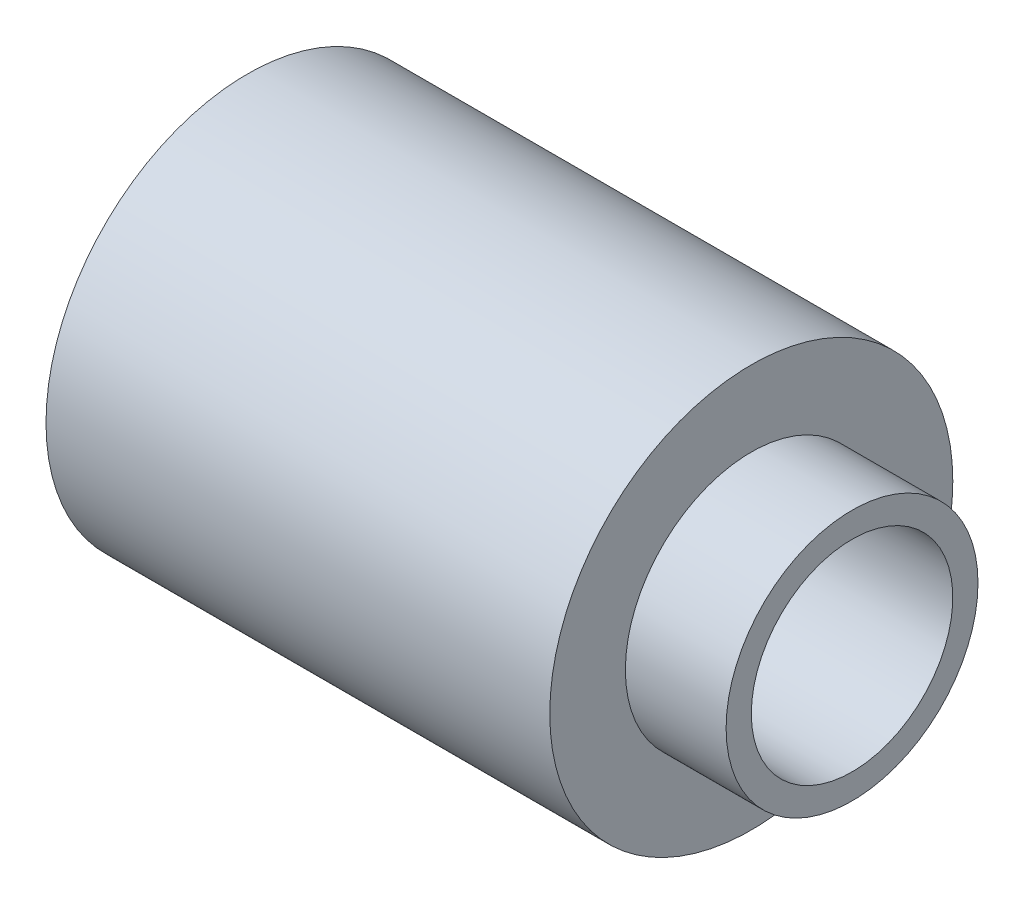
SolidWorks part; units mm, degrees
material "Alloy Steel"
ref_plane "Front Plane" through (0, 0, 0) normal (0, 0, 1) x (1, 0, 0)
ref_plane "Top Plane" through (0, 0, 0) normal (0, 1, 0) x (1, 0, 0)
ref_plane "Right Plane" through (0, 0, 0) normal (1, 0, 0) x (0, 0, -1)
sketch "Sketch1" plane through (0, 0, 0) normal (0, 0, 1) x (1, 0, 0)
  line L0 (-4.7728, 0) -> (5.3097, 0) construction
  line L1 (-10, 2) -> (-10, 4)
  line L2 (-10, 4) -> (0, 4)
  line L3 (0, 4) -> (0, 2.5)
  line L4 (0, 2.5) -> (2, 2.5)
  line L5 (2, 2.5) -> (2, 2)
  line L6 (2, 2) -> (-10, 2)
  point P5 (1, 2.5)
  dimension "D1" = 2
  dimension "D2" = 2.5
  dimension "D3" = 4
  dimension "D4" = 2
  dimension "D5" = 12
revolve "Revolve1" add sketch "Sketch1" angle 360 about L0
